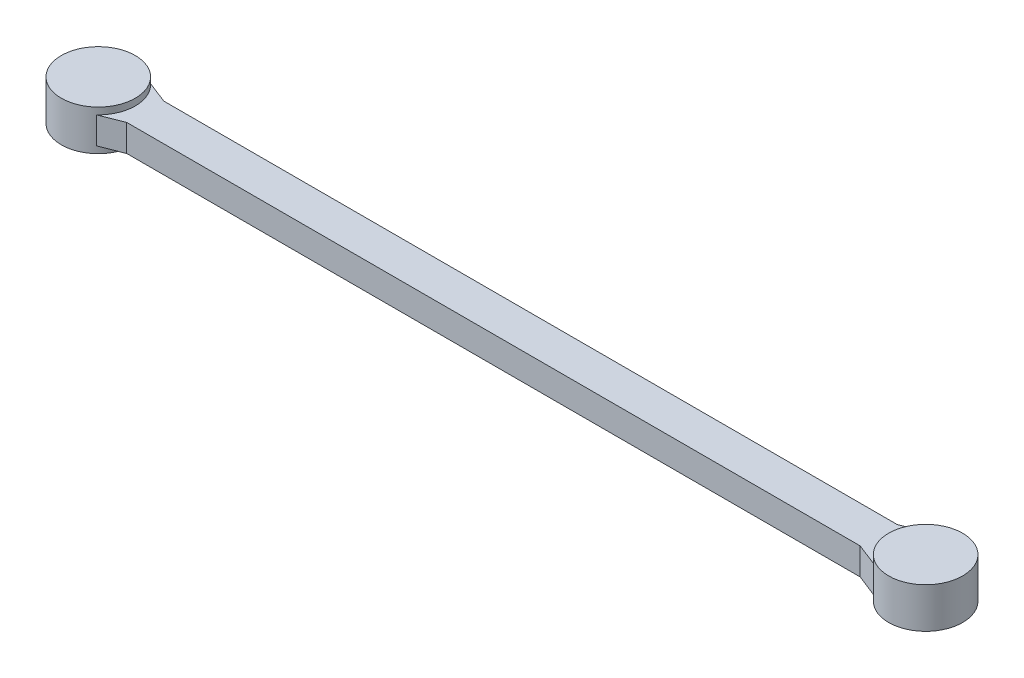
SolidWorks part; units mm, degrees
ref_plane "Front Plane" through (0, 0, 0) normal (0, 0, 1) x (1, 0, 0)
ref_plane "Top Plane" through (0, 0, 0) normal (0, 1, 0) x (1, 0, 0)
ref_plane "Right Plane" through (0, 0, 0) normal (1, 0, 0) x (0, 0, -1)
sketch "Sketch2" plane through (0, 0, 0) normal (0, 1, 0) x (1, 0, 0)
  line L0 (-545, 0) -> (545, 0)
  line L1 (545, 0) -> (614.7764, 27.5)
  line L2 (614.7764, 27.5) -> (614.7764, -82.5)
  line L3 (614.7764, -82.5) -> (545, -55)
  line L4 (545, -55) -> (-545, -55)
  line L6 (-545, 0) -> (-614.7764, 27.5)
  line L7 (-614.7764, 27.5) -> (-614.7764, -82.5)
  line L8 (-614.7764, -82.5) -> (-545, -55)
  dimension "D2" = 75
  dimension "D4" = 75
  dimension "D5" = 110
extrude "Boss-Extrude1" add sketch "Sketch2" along normal blind 40
sketch "Sketch3" plane through (0, 40, 0) normal (0, 1, 0) x (1, 0, 0)
  line L0 (-614.7764, 27.5) -> (-614.7764, -82.5) construction
  line L1 (614.7764, -82.5) -> (614.7764, 27.5) construction
  circle A0 centre (-614.7764, -27.5) radius 55
  circle A1 centre (614.7764, -27.5) radius 55
extrude "Boss-Extrude2" add sketch "Sketch3" along normal blind 10 and the other way blind 50
